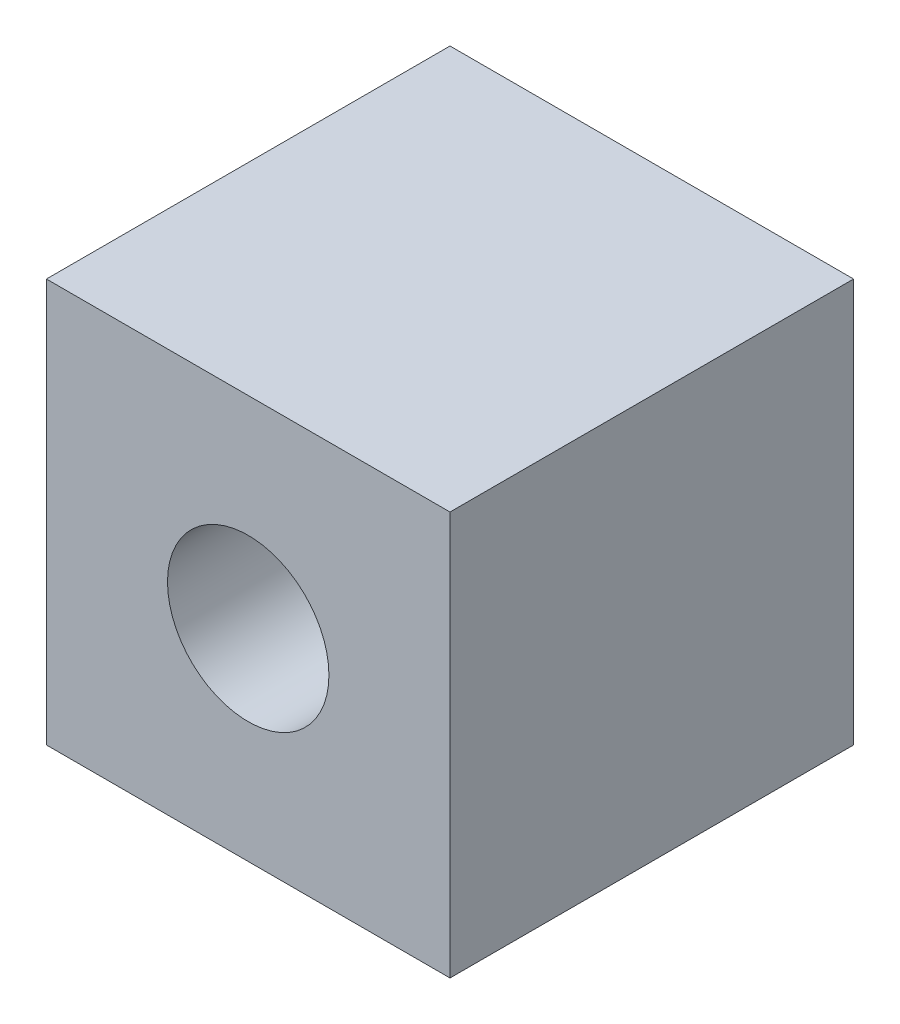
SolidWorks part; units mm, degrees
ref_plane "前视基准面" through (0, 0, 0) normal (0, 0, 1) x (1, 0, 0)
ref_plane "上视基准面" through (0, 0, 0) normal (0, 1, 0) x (1, 0, 0)
ref_plane "右视基准面" through (0, 0, 0) normal (1, 0, 0) x (0, 0, -1)
sketch "草图1" plane through (0, 0, 0) normal (0, 0, 1) x (1, 0, 0)
  line L1 (0, 0) -> (5, 0)
  line L2 (0, 0) -> (0, 5)
  line L3 (0, 5) -> (5, 5)
  line L4 (5, 0) -> (5, 5)
  circle A0 centre (2.5, 2.5) radius 1
  point P9 (2.5, 2.5)
  dimension "D3" = 2
  dimension "D1" = 5
  dimension "D2" = 5
extrude "凸台-拉伸1" add sketch "草图1" against normal blind 5 contours L2 L1 L4 L3
sketch "草图3" plane through (0, 0, 0) normal (0, 0, 1) x (1, 0, 0)
  line L0 (0, 2.5) -> (5, 2.5)
  line L1 (0, 0) -> (0, 5) construction
  line L2 (5, 0) -> (5, 5) construction
  circle A0 centre (2.5, 2.5) radius 1
  dimension "D1" = 2
extrude "切除-拉伸1" cut sketch "草图3" against normal up to surface (5 mm away) contours A0 up to face at (2.5, 2.5, -5)
